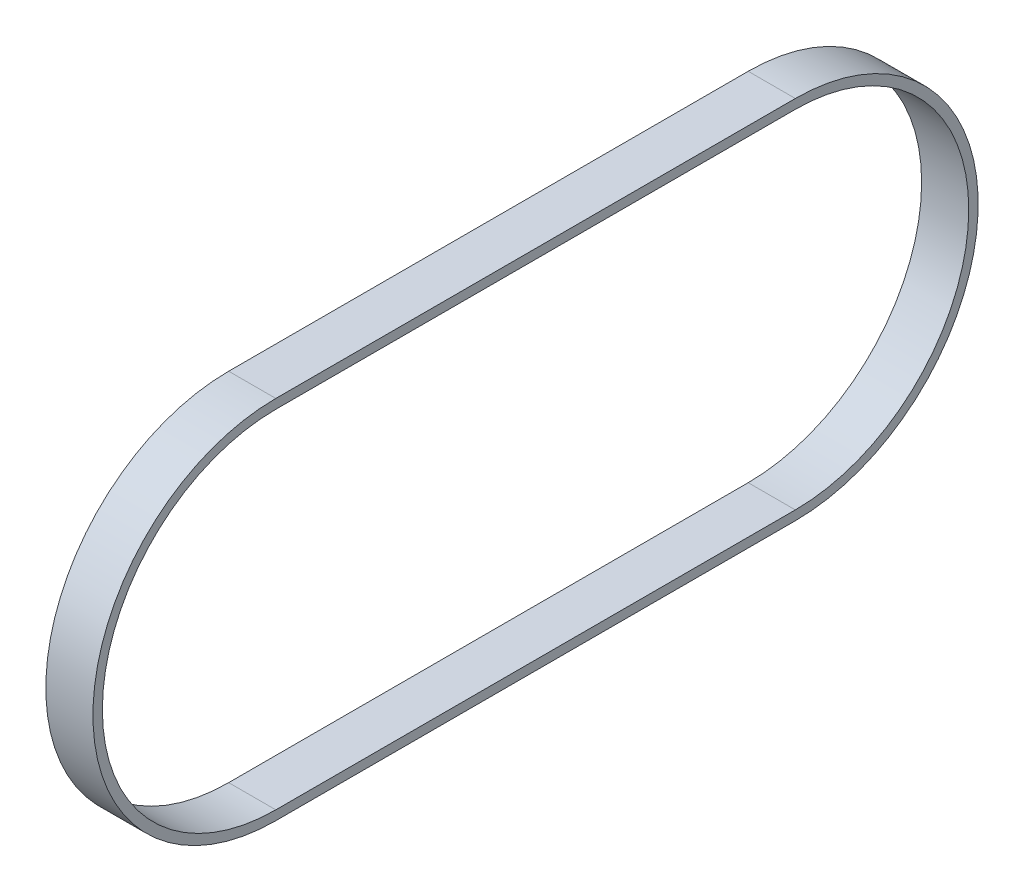
SolidWorks part; units mm, degrees
ref_plane "Front Plane" through (0, 0, 0) normal (0, 0, 1) x (1, 0, 0)
ref_plane "Top Plane" through (0, 0, 0) normal (0, 1, 0) x (1, 0, 0)
ref_plane "Right Plane" through (0, 0, 0) normal (1, 0, 0) x (0, 0, -1)
sketch "Sketch1" plane through (0, 0, 0) normal (1, 0, 0) x (0, 0, -1)
  line L0 (0, 11.684) -> (35, 11.684)
  line L1 (35, -11.684) -> (0, -11.684)
  line L2 (0, -12.319) -> (35, -12.319)
  line L3 (35, 12.319) -> (0, 12.319)
  arc A0 (0, 11.684) -> (0, -11.684) centre (0, 0) ccw
  arc A1 (0, 12.319) -> (0, -12.319) centre (0, 0) ccw
  arc A2 (35, 11.684) -> (35, -11.684) centre (35, 0) cw
  arc A3 (35, -12.319) -> (35, 12.319) centre (35, 0) ccw
  dimension "D1" = 11.684
  dimension "D2" = 0.635
  dimension "D3" = 35
extrude "Boss-Extrude1" add sketch "Sketch1" along normal blind 3.175
